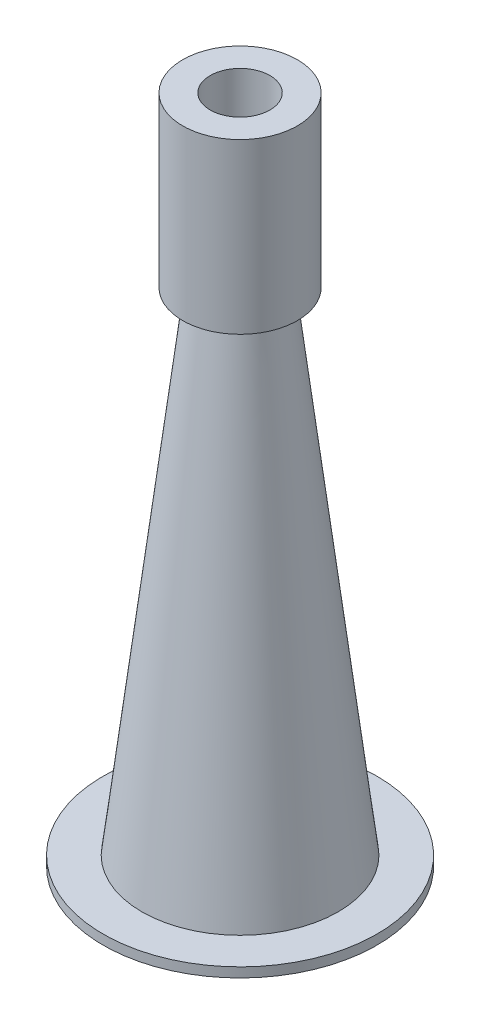
SolidWorks part; units mm, degrees
ref_plane "Front Plane" through (0, 0, 0) normal (0, 0, 1) x (1, 0, 0)
ref_plane "Top Plane" through (0, 0, 0) normal (0, 1, 0) x (1, 0, 0)
ref_plane "Right Plane" through (0, 0, 0) normal (1, 0, 0) x (0, 0, -1)
sketch "Sketch1" plane through (0, 0, 0) normal (0, 0, 1) x (1, 0, 0)
  line L0 (0, 0) -> (0, 700) construction
  line L2 (31, 695) -> (59.5, 695)
  line L3 (59.5, 695) -> (59.5, 520)
  line L4 (59.5, 520) -> (41, 520)
  line L5 (31, 695) -> (31, 520)
  line L6 (31, 520) -> (95, 0)
  line L7 (95, 0) -> (142, 0)
  line L8 (142, 0) -> (142, 10)
  line L9 (142, 10) -> (101.9083, 10)
  line L10 (101.9083, 10) -> (41, 520)
  point P6 (0, 700)
  dimension "D1" = 700
  dimension "D2" = 142
  dimension "D3" = 95
  dimension "D4" = 10
  dimension "D5" = 101.9083
  dimension "D6" = 142
  dimension "D7" = 520
  dimension "D8" = 175
  dimension "D9" = 28.5
revolve "Revolve2" add sketch "Sketch1" angle 360 about L0
